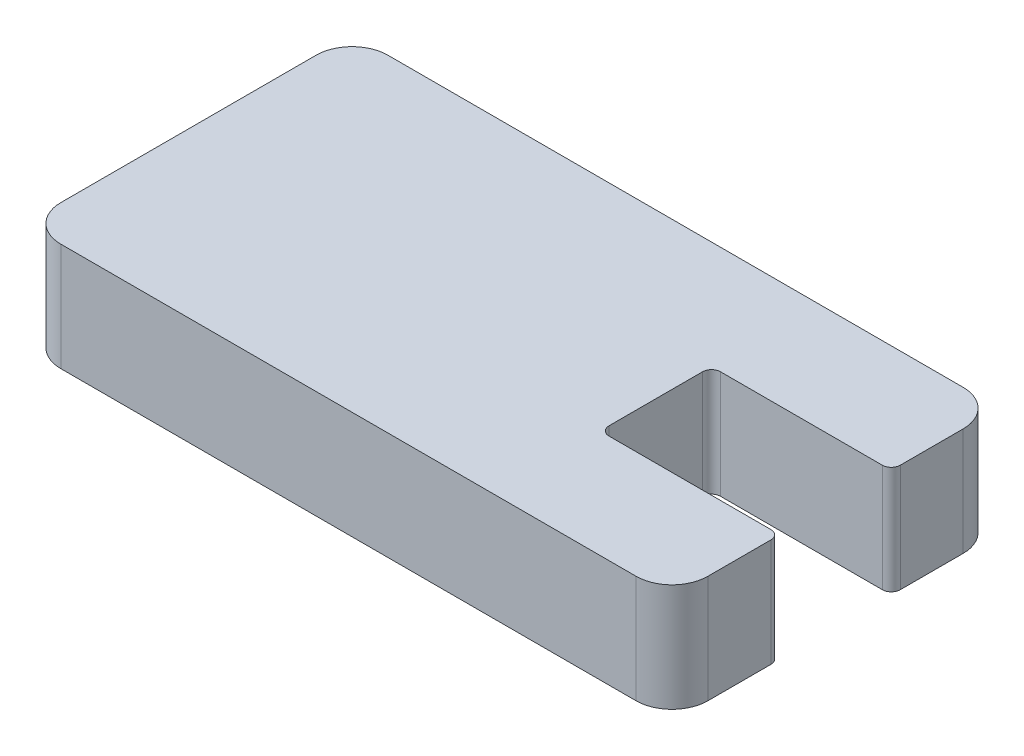
SolidWorks part; units mm, degrees
ref_plane "Alzado" through (0, 0, 0) normal (0, 0, 1) x (1, 0, 0)
ref_plane "Planta" through (0, 0, 0) normal (0, 1, 0) x (1, 0, 0)
ref_plane "Vista lateral" through (0, 0, 0) normal (1, 0, 0) x (0, 0, -1)
sketch "Croquis1" plane through (0, 0, 0) normal (0, 1, 0) x (1, 0, 0)
  line L0 (0, 3.55) -> (0, -3.55)
  line L1 (1, -4.55) -> (17, -4.55)
  line L2 (18, -3.55) -> (18, -1.55)
  line L3 (18, -1.55) -> (13, -1.55)
  line L4 (13, -1.55) -> (13, 1.55)
  line L5 (13, 1.55) -> (18, 1.55)
  line L6 (18, 1.55) -> (18, 3.55)
  line L7 (17, 4.55) -> (1, 4.55)
  arc A0 (18, 3.55) -> (17, 4.55) centre (17, 3.55) ccw
  arc A1 (17, -4.55) -> (18, -3.55) centre (17, -3.55) ccw
  arc A2 (0, -3.55) -> (1, -4.55) centre (1, -3.55) ccw
  arc A3 (0, 3.55) -> (1, 4.55) centre (1, 3.55) cw
  point P4 (0, 0)
  point P12 (18, 4.55)
  point P15 (18, -4.55)
  point P20 (0, 4.55)
  dimension "D7" = 1
  dimension "D1" = 3
  dimension "D2" = 3.1
  dimension "D3" = 3
  dimension "D4" = 18
  dimension "D5" = 5
  dimension "D6" = 5
extrude "Saliente-Extruir1" add sketch "Croquis1" along normal blind 3
fillet "Redondeo1" radius 0.25 4 edges at (18, 1.5, 1.55) (13, 1.5, 1.55) (13, 1.5, -1.55) (18, 1.5, -1.55)
